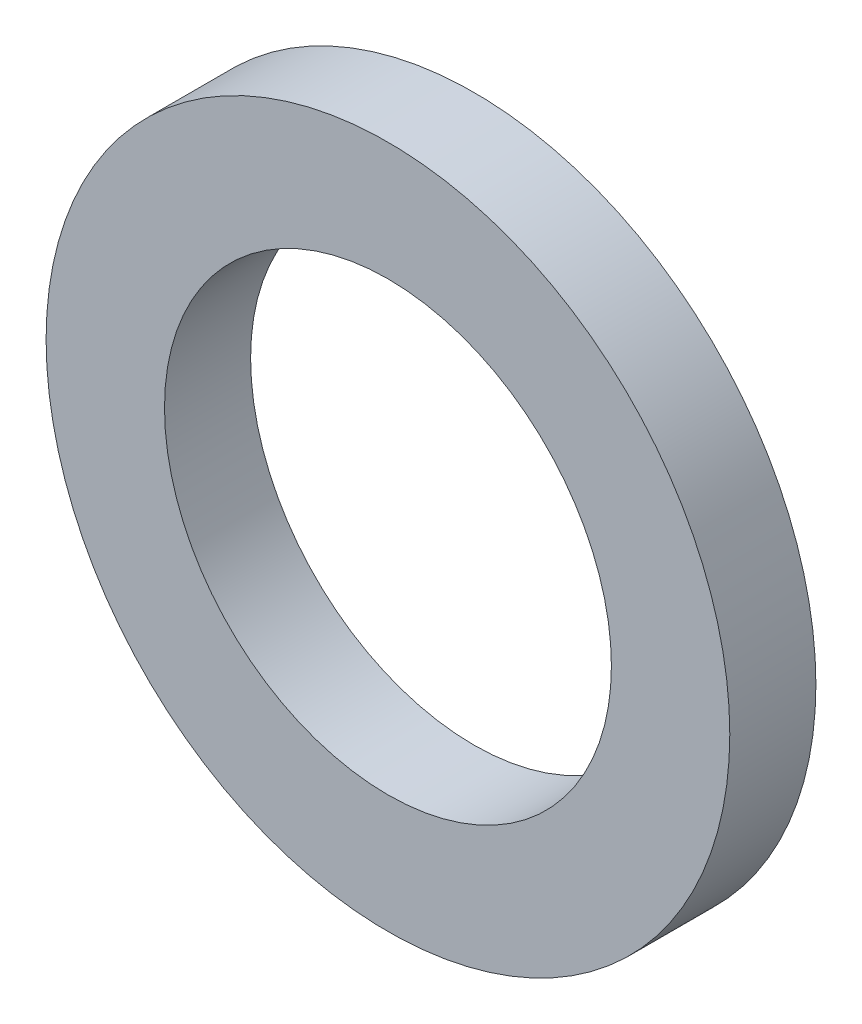
SolidWorks part; units mm, degrees
ref_plane "Płaszczyzna przednia" through (0, 0, 0) normal (0, 0, 1) x (1, 0, 0)
ref_plane "Płaszczyzna górna" through (0, 0, 0) normal (0, 1, 0) x (1, 0, 0)
ref_plane "Płaszczyzna prawa" through (0, 0, 0) normal (1, 0, 0) x (0, 0, -1)
sketch "Szkic1" plane through (0, 0, 0) normal (0, 0, 1) x (1, 0, 0)
  circle A0 centre (0, 0) radius 5.19
  circle A1 centre (0, 0) radius 7.94
  dimension "D1" = 10.38
  dimension "D2" = 15.88
extrude "Dodanie-wyciągnięcie2" add sketch "Szkic1" along normal blind 2
